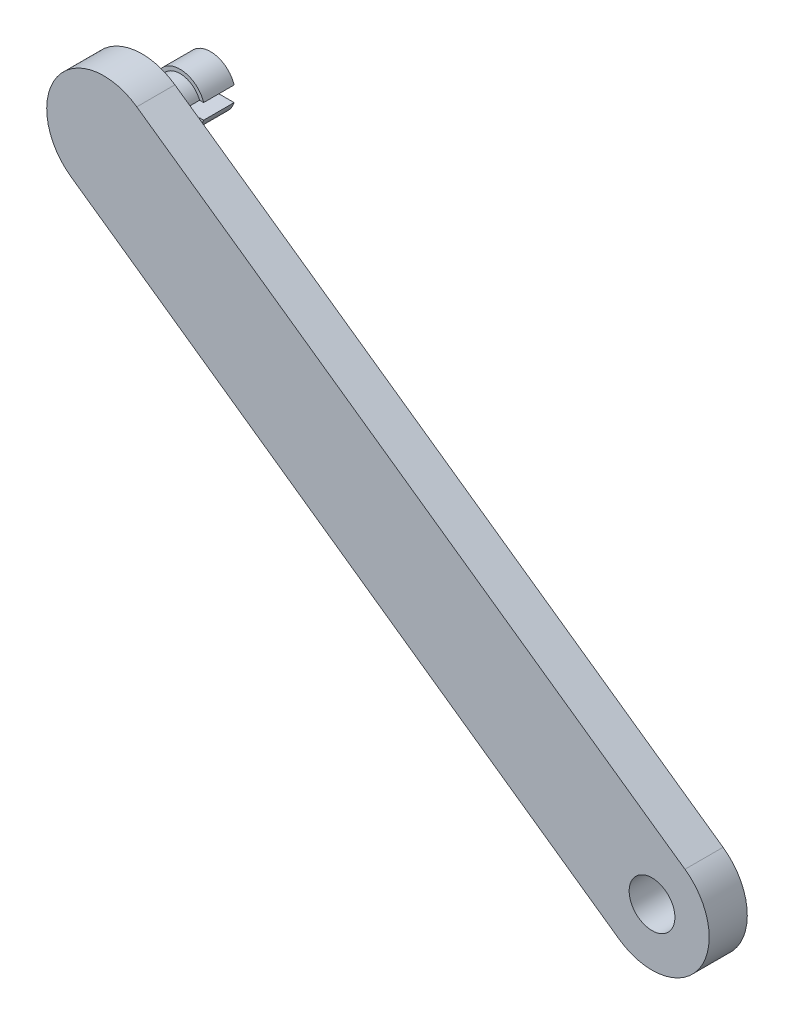
SolidWorks part; units mm, degrees
ref_plane "Plan de face" through (0, 0, 0) normal (0, 0, 1) x (1, 0, 0)
ref_plane "Plan de dessus" through (0, 0, 0) normal (0, 1, 0) x (1, 0, 0)
ref_plane "Plan de droite" through (0, 0, 0) normal (1, 0, 0) x (0, 0, -1)
sketch "Esquisse1" plane through (0, 0, 0) normal (0, 0, 1) x (1, 0, 0)
  line L0 (20, 0) -> (-51.9374, 50.6854) construction
  line L1 (15.6802, -6.131) -> (-56.2572, 44.5544)
  line L2 (24.3198, 6.131) -> (-47.6176, 56.8164)
  arc A0 (15.6802, -6.131) -> (24.3198, 6.131) centre (20, 0) ccw
  arc A1 (-47.6176, 56.8164) -> (-56.2572, 44.5544) centre (-51.9374, 50.6854) ccw
  point P4 (-15.9687, 25.3427)
  dimension "D1" = 15
extrude "Boss.-Extru.1" add sketch "Esquisse1" along normal blind 5
sketch "Esquisse2" plane through (0, 0, 5) normal (0, 0, 1) x (1, 0, 0)
  circle A0 centre (20, 0) radius 3
  dimension "D1" = 6
extrude "Enlèv. mat.-Extru.1" cut sketch "Esquisse2" against normal blind 5
sketch "Esquisse3" plane through (0, 0, 0) normal (0, 0, -1) x (-1, 0, 0)
  circle A0 centre (51.9374, 50.6854) radius 2.75
  dimension "D1" = 5.5
extrude "Boss.-Extru.2" add sketch "Esquisse3" along normal blind 5
sketch "Esquisse4" plane through (0, 0, -5) normal (0, 0, -1) x (-1, 0, 0)
  circle A0 centre (51.9374, 50.6854) radius 3.25
  dimension "D1" = 6.5
extrude "Boss.-Extru.3" add sketch "Esquisse4" along normal blind 4
sketch "Esquisse5" plane through (0, 0, -9) normal (0, 0, -1) x (-1, 0, 0)
  line L1 (46.9374, 51.6854) -> (56.9374, 51.6854)
  line L2 (46.9374, 51.6854) -> (46.9374, 49.6854)
  line L3 (46.9374, 49.6854) -> (56.9374, 49.6854)
  line L4 (56.9374, 51.6854) -> (56.9374, 49.6854)
  dimension "D1" = 1
  dimension "D2" = 1
  dimension "D3" = 10
  dimension "D4" = 5
extrude "Enlèv. mat.-Extru.2" cut sketch "Esquisse5" against normal blind 9
